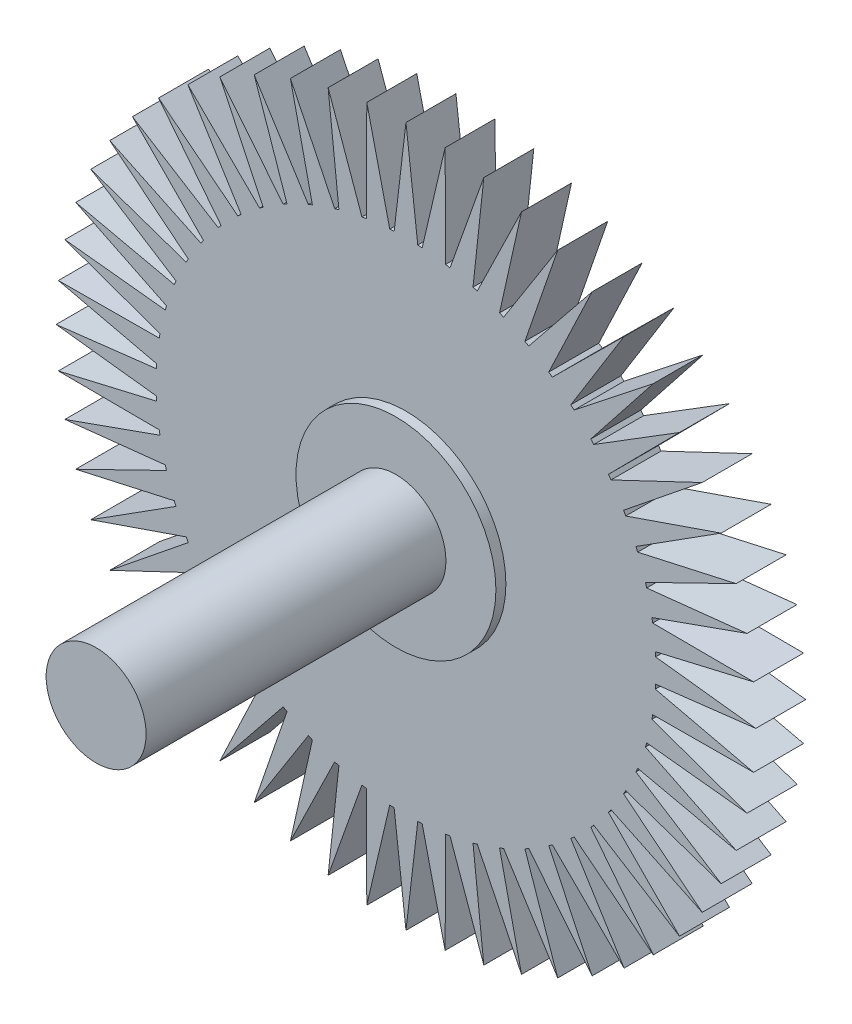
SolidWorks part; units mm, degrees
material "ABS"
ref_plane "Plan de face" through (0, 0, 0) normal (0, 0, 1) x (1, 0, 0)
ref_plane "Plan de dessus" through (0, 0, 0) normal (0, 1, 0) x (1, 0, 0)
ref_plane "Plan de droite" through (0, 0, 0) normal (1, 0, 0) x (0, 0, -1)
sketch "Esquisse1" plane through (0, 0, 0) normal (0, 0, 1) x (1, 0, 0)
  circle A0 centre (0, 0) radius 35
  dimension "D1" = 70
extrude "Boss.-Extru.1" add sketch "Esquisse1" along normal blind 5
sketch "Esquisse3" plane through (0, 0, 5) normal (0, 0, 1) x (1, 0, 0)
  line L0 (0, 35) -> (0, 14.6737) construction
  line L1 (0, 35) -> (-1.1808, 24.9721)
  line L2 (0, 35) -> (1.1808, 24.9721)
  line L3 (3.9188, 34.7799) -> (1.6226, 24.9473)
  line L4 (3.9188, 34.7799) -> (3.9694, 24.6829)
  line L5 (7.7882, 34.1225) -> (4.4056, 24.6088)
  line L6 (7.7882, 34.1225) -> (6.7081, 24.0832)
  line L7 (11.5598, 33.0359) -> (7.1332, 23.9608)
  line L8 (11.5598, 33.0359) -> (9.3623, 23.1807)
  line L9 (15.1859, 31.5339) -> (9.7711, 23.0114)
  line L10 (15.1859, 31.5339) -> (11.8989, 21.9867)
  line L11 (18.6211, 29.6353) -> (12.2861, 21.7727)
  line L12 (18.6211, 29.6353) -> (14.2858, 20.5162)
  line L13 (21.8221, 27.3641) -> (14.6466, 20.2602)
  line L14 (21.8221, 27.3641) -> (16.4931, 18.7877)
  line L15 (24.7487, 24.7487) -> (16.823, 18.4929)
  line L16 (24.7487, 24.7487) -> (18.4929, 16.823)
  line L17 (27.3641, 21.8221) -> (18.7877, 16.4931)
  line L18 (27.3641, 21.8221) -> (20.2602, 14.6466)
  line L19 (29.6353, 18.6211) -> (20.5162, 14.2858)
  line L20 (29.6353, 18.6211) -> (21.7727, 12.2861)
  line L21 (31.5339, 15.1859) -> (21.9867, 11.8989)
  line L22 (31.5339, 15.1859) -> (23.0114, 9.7711)
  line L23 (33.0359, 11.5598) -> (23.1807, 9.3623)
  line L24 (33.0359, 11.5598) -> (23.9608, 7.1332)
  line L25 (34.1225, 7.7882) -> (24.0832, 6.7081)
  line L26 (34.1225, 7.7882) -> (24.6088, 4.4056)
  line L27 (34.7799, 3.9188) -> (24.6829, 3.9694)
  line L28 (34.7799, 3.9188) -> (24.9473, 1.6226)
  line L29 (35, 0) -> (24.9721, 1.1808)
  line L30 (35, 0) -> (24.9721, -1.1808)
  line L31 (34.7799, -3.9188) -> (24.9473, -1.6226)
  line L32 (34.7799, -3.9188) -> (24.6829, -3.9694)
  line L33 (34.1225, -7.7882) -> (24.6088, -4.4056)
  line L34 (34.1225, -7.7882) -> (24.0832, -6.7081)
  line L35 (33.0359, -11.5598) -> (23.9608, -7.1332)
  line L36 (33.0359, -11.5598) -> (23.1807, -9.3623)
  line L37 (31.5339, -15.1859) -> (23.0114, -9.7711)
  line L38 (31.5339, -15.1859) -> (21.9867, -11.8989)
  line L39 (29.6353, -18.6211) -> (21.7727, -12.2861)
  line L40 (29.6353, -18.6211) -> (20.5162, -14.2858)
  line L41 (27.3641, -21.8221) -> (20.2602, -14.6466)
  line L42 (27.3641, -21.8221) -> (18.7877, -16.4931)
  line L43 (24.7487, -24.7487) -> (18.4929, -16.823)
  line L44 (24.7487, -24.7487) -> (16.823, -18.4929)
  line L45 (21.8221, -27.3641) -> (16.4931, -18.7877)
  line L46 (21.8221, -27.3641) -> (14.6466, -20.2602)
  line L47 (18.6211, -29.6353) -> (14.2858, -20.5162)
  line L48 (18.6211, -29.6353) -> (12.2861, -21.7727)
  line L49 (15.1859, -31.5339) -> (11.8989, -21.9867)
  line L50 (15.1859, -31.5339) -> (9.7711, -23.0114)
  line L51 (11.5598, -33.0359) -> (9.3623, -23.1807)
  line L52 (11.5598, -33.0359) -> (7.1332, -23.9608)
  line L53 (7.7882, -34.1225) -> (6.7081, -24.0832)
  line L54 (7.7882, -34.1225) -> (4.4056, -24.6088)
  line L55 (3.9188, -34.7799) -> (3.9694, -24.6829)
  line L56 (3.9188, -34.7799) -> (1.6226, -24.9473)
  line L57 (0, -35) -> (1.1808, -24.9721)
  line L58 (0, -35) -> (-1.1808, -24.9721)
  line L59 (-3.9188, -34.7799) -> (-1.6226, -24.9473)
  line L60 (-3.9188, -34.7799) -> (-3.9694, -24.6829)
  line L61 (-7.7882, -34.1225) -> (-4.4056, -24.6088)
  line L62 (-7.7882, -34.1225) -> (-6.7081, -24.0832)
  line L63 (-11.5598, -33.0359) -> (-7.1332, -23.9608)
  line L64 (-11.5598, -33.0359) -> (-9.3623, -23.1807)
  line L65 (-15.1859, -31.5339) -> (-9.7711, -23.0114)
  line L66 (-15.1859, -31.5339) -> (-11.8989, -21.9867)
  line L67 (-18.6211, -29.6353) -> (-12.2861, -21.7727)
  line L68 (-18.6211, -29.6353) -> (-14.2858, -20.5162)
  line L69 (-21.8221, -27.3641) -> (-14.6466, -20.2602)
  line L70 (-21.8221, -27.3641) -> (-16.4931, -18.7877)
  line L71 (-24.7487, -24.7487) -> (-16.823, -18.4929)
  line L72 (-24.7487, -24.7487) -> (-18.4929, -16.823)
  line L73 (-27.3641, -21.8221) -> (-18.7877, -16.4931)
  line L74 (-27.3641, -21.8221) -> (-20.2602, -14.6466)
  line L75 (-29.6353, -18.6211) -> (-20.5162, -14.2858)
  line L76 (-29.6353, -18.6211) -> (-21.7727, -12.2861)
  line L77 (-31.5339, -15.1859) -> (-21.9867, -11.8989)
  line L78 (-31.5339, -15.1859) -> (-23.0114, -9.7711)
  line L79 (-33.0359, -11.5598) -> (-23.1807, -9.3623)
  line L80 (-33.0359, -11.5598) -> (-23.9608, -7.1332)
  line L81 (-34.1225, -7.7882) -> (-24.0832, -6.7081)
  line L82 (-34.1225, -7.7882) -> (-24.6088, -4.4056)
  line L83 (-34.7799, -3.9188) -> (-24.6829, -3.9694)
  line L84 (-34.7799, -3.9188) -> (-24.9473, -1.6226)
  line L85 (-35, 0) -> (-24.9721, -1.1808)
  line L86 (-35, 0) -> (-24.9721, 1.1808)
  line L87 (-34.7799, 3.9188) -> (-24.9473, 1.6226)
  line L88 (-34.7799, 3.9188) -> (-24.6829, 3.9694)
  line L89 (-34.1225, 7.7882) -> (-24.6088, 4.4056)
  line L90 (-34.1225, 7.7882) -> (-24.0832, 6.7081)
  line L91 (-33.0359, 11.5598) -> (-23.9608, 7.1332)
  line L92 (-33.0359, 11.5598) -> (-23.1807, 9.3623)
  line L93 (-31.5339, 15.1859) -> (-23.0114, 9.7711)
  line L94 (-31.5339, 15.1859) -> (-21.9867, 11.8989)
  line L95 (-29.6353, 18.6211) -> (-21.7727, 12.2861)
  line L96 (-29.6353, 18.6211) -> (-20.5162, 14.2858)
  line L97 (-27.3641, 21.8221) -> (-20.2602, 14.6466)
  line L98 (-27.3641, 21.8221) -> (-18.7877, 16.4931)
  line L99 (-24.7487, 24.7487) -> (-18.4929, 16.823)
  line L100 (-24.7487, 24.7487) -> (-16.823, 18.4929)
  line L101 (-21.8221, 27.3641) -> (-16.4931, 18.7877)
  line L102 (-21.8221, 27.3641) -> (-14.6466, 20.2602)
  line L103 (-18.6211, 29.6353) -> (-14.2858, 20.5162)
  line L104 (-18.6211, 29.6353) -> (-12.2861, 21.7727)
  line L105 (-15.1859, 31.5339) -> (-11.8989, 21.9867)
  line L106 (-15.1859, 31.5339) -> (-9.7711, 23.0114)
  line L107 (-11.5598, 33.0359) -> (-9.3623, 23.1807)
  line L108 (-11.5598, 33.0359) -> (-7.1332, 23.9608)
  line L109 (-7.7882, 34.1225) -> (-6.7081, 24.0832)
  line L110 (-7.7882, 34.1225) -> (-4.4056, 24.6088)
  line L111 (-3.9188, 34.7799) -> (-3.9694, 24.6829)
  line L112 (-3.9188, 34.7799) -> (-1.6226, 24.9473)
  circle A0 centre (0, 0) radius 25
  circle A1 centre (0, 0) radius 35 construction
  point P177 (0, 0)
  circle M3 centre (0, 0) radius 35
  dimension "D1" = 50
  dimension "D2" = 10
  dimension "D3" = 10.0279
  dimension "D4" = 56
extrude "Enlèv. mat.-Extru.2" cut sketch "Esquisse3" against normal blind 5 contours A0 L105 L104 M3 | A0 L107 L106 M3 | A0 L109 L108 M3 | A0 L111 L110 M3 | A0 L1 L112 M3 | A0 L3 L2 M3 | A0 L5 L4 M3 | A0 L7 L6 M3 | A0 L9 L8 M3 | A0 L11 L10 M3 | A0 L13 L12 M3 | A0 L15 L14 M3 | A0 L103 L102 M3 | A0 L101 L100 M3 | A0 L99 L98 M3 | A0 L97 L96 M3 | A0 L95 L94 M3 | A0 L93 L92 M3 | A0 L91 L90 M3 | A0 L89 L88 M3 | A0 L87 L86 M3 | A0 L85 L84 M3 | A0 L83 L82 M3 | A0 L81 L80 M3 | A0 L79 L78 M3 | A0 L77 L76 M3 | A0 L75 L74 M3 | A0 L73 L72 M3 | A0 L71 L70 M3 | A0 L69 L68 M3 | A0 L67 L66 M3 | A0 L65 L64 M3 | A0 L63 L62 M3 | A0 L61 L60 M3 | A0 L59 L58 M3 | A0 L57 L56 M3 | A0 L55 L54 M3 | A0 L53 L52 M3 | A0 L51 L50 M3 | A0 L49 L48 M3 | A0 L47 L46 M3 | A0 L45 L44 M3 | A0 L43 L42 M3 | A0 L41 L40 M3 | A0 L39 L38 M3 | A0 L37 L36 M3 | A0 L35 L34 M3 | A0 L33 L32 M3 | A0 L17 L16 M3 | A0 L19 L18 M3 | A0 L21 L20 M3 | A0 L23 L22 M3 | A0 L25 L24 M3 | A0 L27 L26 M3 | A0 L29 L28 M3 | A0 L31 L30 M3
sketch "Esquisse5" plane through (0, 0, 5) normal (0, 0, 1) x (1, 0, 0)
  circle A0 centre (0, 0) radius 10
  dimension "D1" = 20
extrude "Boss.-Extru.2" add sketch "Esquisse5" along normal blind 1
sketch "Esquisse6" plane through (0, 0, 6) normal (0, 0, 1) x (1, 0, 0)
  circle A0 centre (0, 0) radius 5
  dimension "D1" = 10
extrude "Boss.-Extru.3" add sketch "Esquisse6" along normal blind 30
